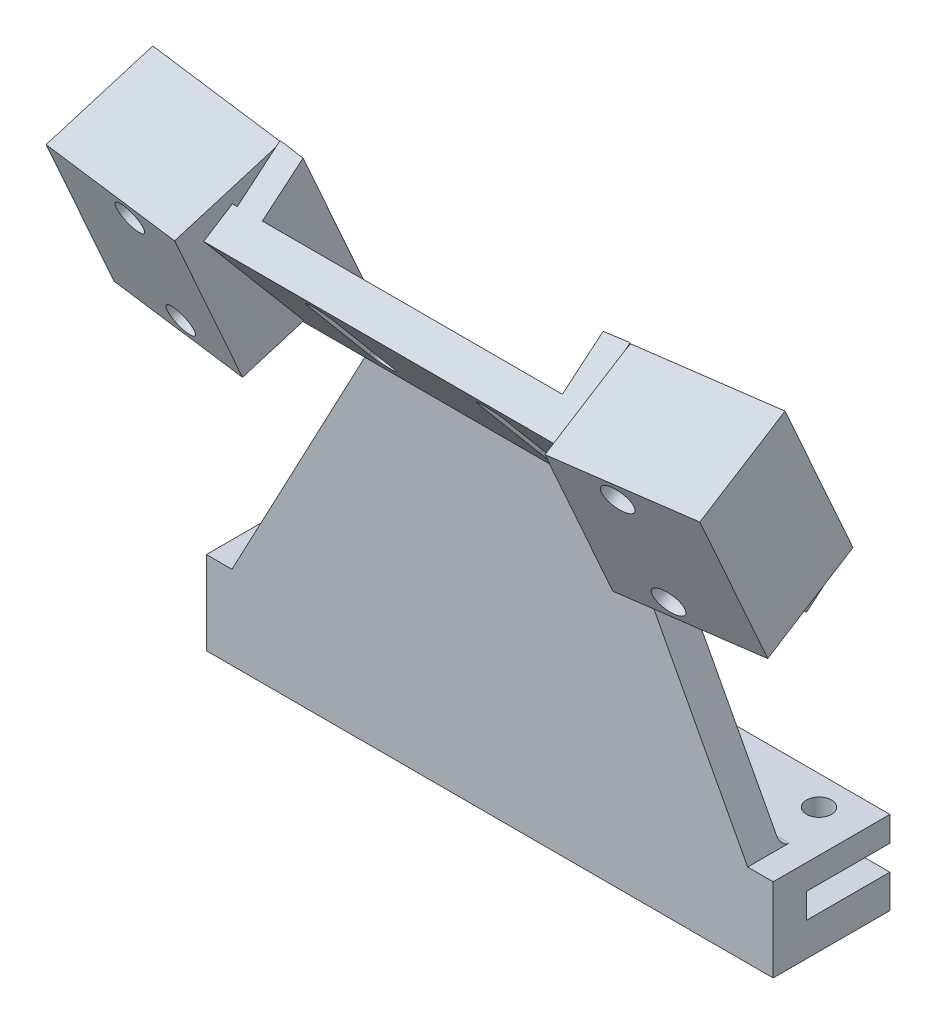
SolidWorks part; units mm, degrees
ref_plane "前视基准面" through (0, 0, 0) normal (0, 0, 1) x (1, 0, 0)
ref_plane "上视基准面" through (0, 0, 0) normal (0, 1, 0) x (1, 0, 0)
ref_plane "右视基准面" through (0, 0, 0) normal (1, 0, 0) x (0, 0, -1)
sketch "草图1" plane through (0, 0, 0) normal (1, 0, 0) x (0, 0, -1)
  line L0 (0, 0) -> (0, 4)
  line L1 (0, 4) -> (-10, 4)
  line L2 (-10, 4) -> (-10, 7)
  line L3 (-10, 7) -> (0, 7)
  line L4 (0, 7) -> (0, 10)
  line L5 (0, 10) -> (-14, 10)
  line L9 (-14, 0) -> (0, 0)
  line L10 (-14, 10) -> (-14, 0)
  dimension "D1" = 3
  dimension "D2" = 4
  dimension "D3" = 3
  dimension "D4" = 10
  dimension "D5" = 4
extrude "凸台-拉伸1" add sketch "草图1" along normal blind 68
sketch "草图2" plane through (0, 10, 0) normal (0, 1, 0) x (1, 0, 0)
  line L0 (34, 0) -> (34, -14) construction
  line L1 (68, 0) -> (0, 0) construction
  line L2 (68, -14) -> (0, -14) construction
  circle A0 centre (5, -3.5) radius 1.5
  circle A1 centre (63, -3.5) radius 1.5
  dimension "D1" = 3
  dimension "D2" = 3.5
  dimension "D3" = 58
extrude "切除-拉伸1" cut sketch "草图2" against normal blind 60
sketch "草图3" plane through (0, 0, 0) normal (0, -1, 0) x (1, 0, 0)
  line L2 (68, 10) -> (0, 10) construction
  line L3 (49, 10) -> (19, 10)
  line L4 (19, 10) -> (19, 14)
  line L5 (19, 14) -> (49, 14)
  line L14 (49, 14) -> (49, 10)
  line L16 (34, 0) -> (34, 18.0549) construction
  line L17 (68, 0) -> (0, 0) construction
  dimension "D1" = 30
extrude "凸台-拉伸2" add sketch "草图3" against normal blind 40
sketch "草图4" plane through (49, 0, 0) normal (1, 0, 0) x (0, 0, -1)
  line L0 (-14, 40) -> (-26.3577, 54.7273)
  line L1 (-26.3577, 54.7273) -> (-23.2935, 57.2985)
  line L2 (-23.2935, 57.2985) -> (-10, 41.4559)
  line L5 (-14, 40) -> (-10, 40)
  line L7 (-10, 40) -> (-10, 41.4559)
  line L8 (-10, 40) -> (-10, 10) construction
  dimension "D1" = 4
  dimension "D2" = 130
extrude "凸台-拉伸3" add sketch "草图4" against normal up to surface (30 mm away) up to face at (19, 25, 12)
sketch "草图5" plane through (0, 9.6334, -11.4806) normal (0, -0.6428, 0.766) x (1, 0, 0)
  line L3 (23.75, 55.3181) -> (23.75, 43.8648) construction
  line L4 (25.25, 55.3181) -> (25.25, 43.8648)
  line L5 (22.25, 55.3181) -> (22.25, 43.8648)
  line L6 (44.25, 55.3181) -> (44.25, 43.8648) construction
  line L7 (42.75, 55.3181) -> (42.75, 43.8648)
  line L8 (45.75, 55.3181) -> (45.75, 43.8648)
  arc A0 (25.25, 55.3181) -> (22.25, 55.3181) centre (23.75, 55.3181) ccw
  arc A1 (22.25, 43.8648) -> (25.25, 43.8648) centre (23.75, 43.8648) ccw
  arc A2 (42.75, 55.3181) -> (45.75, 55.3181) centre (44.25, 55.3181) cw
  arc A3 (45.75, 43.8648) -> (42.75, 43.8648) centre (44.25, 43.8648) cw
  point P8 (23.75, 49.5915)
  point P15 (44.25, 49.5915)
  dimension "D2" = 3
  dimension "D1" = 20.5
extrude "切除-拉伸2" cut sketch "草图5" against normal up to surface (4 mm away) up to face at (34, 49.3772, 16.6468)
sketch "草图6" plane through (19, 0, 0) normal (-1, 0, 0) x (0, 0, 1)
  line L0 (23.2935, 57.2985) -> (26.3577, 54.7273)
  line L1 (26.3577, 54.7273) -> (14, 40)
  line L2 (14, 40) -> (10.9358, 42.5712)
  line L3 (10, 41.4559) -> (23.2935, 57.2985) construction
  line L4 (10.9358, 42.5712) -> (23.2935, 57.2985)
extrude "凸台-拉伸4" add sketch "草图6" along normal blind 23 contours L4 L0 L1 L2
sketch "草图7" plane through (-4, 0, 0) normal (-1, 0, 0) x (0, 0, 1)
  line L0 (23.2935, 57.2985) -> (26.3577, 54.7273)
  line L1 (26.3577, 54.7273) -> (14, 40)
  line L2 (26.3577, 54.7273) -> (14, 40) construction
  line L3 (14, 40) -> (10.9358, 42.5712) construction
  line L4 (14, 40) -> (10.9358, 42.5712)
  line L5 (10.9358, 42.5712) -> (23.2935, 57.2985)
extrude "凸台-拉伸5" add sketch "草图7" against normal blind 23 from surface at -53 contours L5 L0 L1 L4 starting at face at (49, 35.5803, 16.2752)
sketch "草图8" plane through (0, 12.2045, -14.5448) normal (0, 0.6428, -0.766) x (-1, 0, 0)
  line L0 (-72, 39.6408) -> (-52, 39.6408) construction
  line L1 (-72, 39.6408) -> (-49, 39.6408) construction
  line L2 (-52, 39.6408) -> (-52, 58.8659) construction
  line L3 (4, 58.8659) -> (-72, 58.8659) construction
ref_plane "基准面1" through (52, 0, 0) normal (-1, 0, 0) x (0, 0.766, 0.6428)
sketch "草图10" plane through (52, 0, 0) normal (-1, 0, 0) x (0, 0.766, 0.6428)
  line L0 (39.6408, 18.9869) -> (58.8659, 18.9869)
  line L1 (39.6408, 18.9869) -> (39.6408, 20.6535)
  line L2 (58.8659, 18.9869) -> (58.8659, 25.6535)
  line L3 (39.6408, 20.6535) -> (58.8659, 25.6535)
extrude "凸台-拉伸6" add sketch "草图10" against normal blind 3
ref_plane "基准面2" through (72, 0, 0) normal (1, 0, 0) x (0, 0, -1)
sketch "草图11" plane through (72, 0, 0) normal (1, 0, 0) x (0, 0, -1)
  line L0 (-23.2935, 57.2985) -> (-22.2987, 56.1129) construction
  line L2 (-23.2935, 57.2985) -> (-10.9358, 42.5712) construction
  line L3 (-22.2987, 56.1129) -> (-16.6617, 60.8429) construction
  line L4 (-22.2987, 56.1129) -> (-10.2222, 41.7207) construction
  line L5 (-16.6617, 60.8429) -> (-8.4444, 43.2124) construction
  line L8 (-10.2222, 41.7207) -> (-8.4444, 43.2124) construction
ref_plane "基准面3" through (0, 30.3666, 25.4806) normal (0, -0.766, -0.6428) x (-1, 0, 0)
sketch "草图12" plane through (55, 0, 0) normal (1, 0, 0) x (0, 0, -1)
  line L0 (-18.1865, 61.5837) -> (-18.6972, 61.1552) construction
  line L1 (-23.2935, 57.2985) -> (-18.1865, 61.5837) construction
  line L2 (-9.6591, 43.6425) -> (-10.5528, 42.8925) construction
  line L3 (-9.6591, 43.6425) -> (-10.9358, 42.5712) construction
  line L4 (-18.6972, 61.1552) -> (-10.5528, 42.8925) construction
  line L5 (-18.1865, 61.5837) -> (-9.6591, 43.6425) construction
ref_plane "基准面4" through (-0.2247, 0.8985, -2.0148) normal (0.1014, -0.4052, 0.9086) x (0.9949, 0.0413, -0.0926)
sketch "草图15" plane through (-0.2247, 0.8985, -2.0148) normal (0.1014, -0.4052, 0.9086) x (0.9949, 0.0413, -0.0926)
  line L0 (55.5106, 63.4681) -> (55.5106, 62.3539)
  line L1 (55.5106, 43.4717) -> (72.5986, 43.4717)
  line L2 (55.5106, 43.4717) -> (55.5106, 62.3539)
  line L4 (72.5986, 43.4717) -> (72.5986, 62.3539)
  line L5 (72.5986, 62.3539) -> (72.5986, 63.4681)
  line L6 (72.5986, 63.4681) -> (55.5106, 63.4681)
extrude "凸台-拉伸7" add sketch "草图15" against normal blind 0.6667
sketch "草图17" plane through (-0.2247, 0.8985, -2.0148) normal (0.1014, -0.4052, 0.9086) x (0.9949, 0.0413, -0.0926)
  line L1 (55.5106, 63.4681) -> (72.5986, 63.4681)
  line L2 (55.5106, 63.4681) -> (55.5106, 43.4717)
  line L3 (55.5106, 43.4717) -> (72.5986, 43.4717)
  line L4 (72.5986, 63.4681) -> (72.5986, 43.4717)
extrude "凸台-拉伸9" add sketch "草图17" along normal blind 12
sketch "草图19" plane through (-0.2923, 1.1686, -2.6205) normal (-0.1014, 0.4052, -0.9086) x (-0.9949, -0.0413, 0.0926)
  line L0 (-72.5986, 53.4699) -> (-62.5986, 53.4699) construction
  line L1 (-72.5986, 43.4717) -> (-72.5986, 63.4681) construction
  line L2 (-62.5986, 45.9699) -> (-62.5986, 60.9699) construction
  circle A0 centre (-62.5986, 60.9699) radius 1.8
  circle A1 centre (-62.5986, 45.9699) radius 1.8
  point P7 (-62.5986, 53.4699)
extrude "切除-拉伸3" cut sketch "草图19" against normal blind 20
ref_plane "基准面6" through (34, 0, 0) normal (-1, 0, 0) x (0, 0, 1)
sketch "草图20" plane through (34, 0, 0) normal (-1, 0, 0) x (0, 0, 1)
  line L5 (-13.8568, 74.4851) -> (47.7463, 74.4851)
  line L6 (-13.8568, 74.4851) -> (-13.8568, -10.1017)
  line L7 (-13.8568, -10.1017) -> (47.7463, -10.1017)
  line L8 (47.7463, 74.4851) -> (47.7463, -10.1017)
extrude "切除-拉伸4" cut sketch "草图20" along normal blind 65
mirror "镜向7" about plane through (34, 0, 0) normal (-1, 0, 0) of bodies 113
sketch "草图21" plane through (-0.2923, 1.1686, -2.6205) normal (-0.1014, 0.4052, -0.9086) x (-0.9949, -0.0413, 0.0926)
  line L0 (-58.2616, 63.4681) -> (-58.2616, 67.2389) construction
  line L1 (-72.5986, 63.4681) -> (-55.5106, 63.4681) construction
  line L3 (-58.2616, 67.2389) -> (-50.7673, 67.2389)
  line L4 (-58.2616, 67.2389) -> (-58.2616, 40.3658)
  line L5 (-58.2616, 40.3658) -> (-50.7673, 40.3658)
  line L6 (-50.7673, 67.2389) -> (-50.7673, 40.3658)
extrude "切除-拉伸5" cut sketch "草图21" along normal blind 2
sketch "草图22" plane through (0.9908, 3.9612, -8.8824) normal (0.1014, 0.4052, -0.9086) x (-0.9949, 0.0413, -0.0926)
  line L1 (-7.0412, 66.9297) -> (-17.0119, 66.9297)
  line L2 (-7.0412, 66.9297) -> (-7.0412, 41.135)
  line L3 (-7.0412, 41.135) -> (-17.0119, 41.135)
  line L4 (-17.0119, 66.9297) -> (-17.0119, 41.135)
extrude "切除-拉伸6" cut sketch "草图22" along normal blind 2
sketch "草图24" plane through (0, 0, 14) normal (0, 0, 1) x (1, 0, 0)
  line L3 (34, 40) -> (34, -2.8339) construction
  line L4 (49, 40) -> (19, 40) construction
  line L8 (19, 40) -> (3.0592, 10)
  line L9 (8.3952, 10) -> (19, 10)
  line L10 (19, 10) -> (19, 29.9578)
  line L11 (49, 29.9578) -> (49, 10)
  line L12 (0, 10) -> (19, 10) construction
  line L13 (3.0592, 10) -> (8.3952, 10)
  line L14 (49, 10) -> (59.6048, 10)
  line L16 (19, 40) -> (19, 10) construction
  line L17 (19, 40) -> (19, 29.9578)
  line L18 (49, 40) -> (64.9408, 10)
  line L19 (64.9408, 10) -> (59.6048, 10)
  line L21 (49, 40) -> (49, 29.9578)
extrude "凸台-拉伸10" add sketch "草图24" against normal blind 4
sketch "草图26" plane through (0, 0, 10) normal (0, 0, -1) x (-1, 0, 0)
  line L0 (-34, 41.4559) -> (-34, 10) construction
  line L1 (-19, 41.4559) -> (-49, 41.4559) construction
  line L2 (-3.0592, 10) -> (-64.9408, 10) construction
sketch "草图28" plane through (0, 10, 0) normal (0, 1, 0) x (1, 0, 0)
  line L0 (34, 0) -> (34, -10) construction
  line L1 (68, 0) -> (0, 0) construction
  line L2 (3.0592, -10) -> (64.9408, -10) construction
sketch "草图29" plane through (34, 0, 0) normal (-1, 0, 0) x (0, 0, 1)
  line L2 (10, 10) -> (2.7924, 10)
  line L5 (10, 41.4559) -> (10, 10)
  line L6 (0, 10) -> (10, 10) construction
  line L8 (2.7924, 10) -> (10, 41.4559)
fillet "圆角1" radius 1 1 edges at (34, 10, 10)
fillet "圆角2" radius 1 1 edges at (34, 41.4559, 10)
